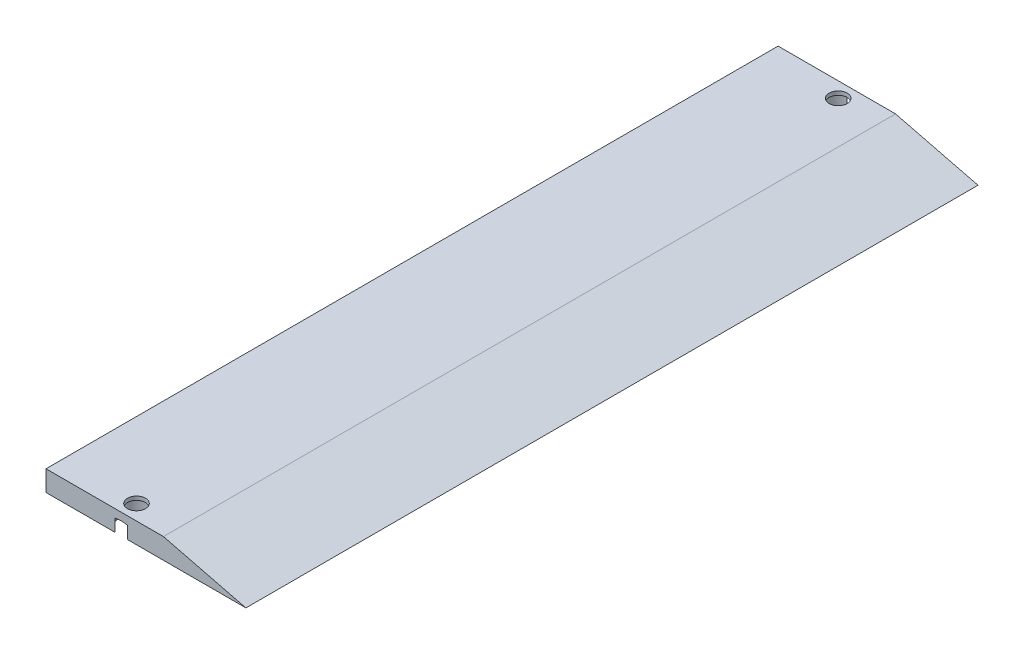
SolidWorks part; units mm, degrees
material "AISI 316 Stainless Steel Sheet (SS)"
ref_plane "Спереди" through (0, 0, 0) normal (0, 0, 1) x (1, 0, 0)
ref_plane "Сверху" through (0, 0, 0) normal (0, 1, 0) x (1, 0, 0)
ref_plane "Справа" through (0, 0, 0) normal (1, 0, 0) x (0, 0, -1)
sketch "Sketch1" plane through (0, 0, 0) normal (0, 0, 1) x (1, 0, 0)
  line L0 (0, 0) -> (0, 2.5)
  line L1 (0, 2.5) -> (14.273, 2.5)
  line L2 (14.273, 2.5) -> (24.3, 0)
  line L3 (24.3, 0) -> (0, 0)
  dimension "D1" = 2.5
  dimension "D2" = 166
  dimension "D3" = 24.3
  dimension "D4" = 14.273
extrude "Boss-Extrude1" add sketch "Sketch1" along normal mid plane 89
sketch "Sketch4" plane through (0, 0, 0) normal (0, -1, 0) x (1, 0, 0)
  line L0 (0, 44.5) -> (0, -44.5) construction
  point P0 (9.15, 42.65)
  point P1 (9.15, -42.65)
  dimension "D1" = 85.3
  dimension "D2" = 42.65
  dimension "D3" = 9.15
hole_wizard "HoleWzd2" positions "3DSketch3" profile "Sketch6" legacy end condition up to next
sketch3d "3DSketch3"
  point P0 (9.15, 0, 42.65)
  point P3 (9.15, 0, -42.65)
sketch "Sketch6" plane through (9.15, 0, 42.65) normal (1, 0, 0) x (0, 0, -1)
  line L0 (0, 0) -> (0, 2.5)
  line L1 (0, 2.5) -> (1.1, 2.5)
  line L2 (1.1, 2.5) -> (1.1, 2.0408)
  line L3 (1.1, 2.0408) -> (2, 1.5)
  line L4 (2, 1.5) -> (2, 0)
  line L5 (2, 0) -> (0, 0)
  line L6 (0, -6.13) -> (0, 109.2824) construction
  line L7 (-1.1, 2.0408) -> (-2, 1.5) construction
  line L8 (0, 2.5) -> (-1.1, 2.5) construction
  dimension "Diameter" = 2.2
  dimension "Depth" = 2.5
  dimension "C-Drill Diameter" = 4
  dimension "C-Drill Depth" = 1.5
  dimension "C-Drill Angle" = 118
equation "\"dist_hole\"= 83 + 2.3"
